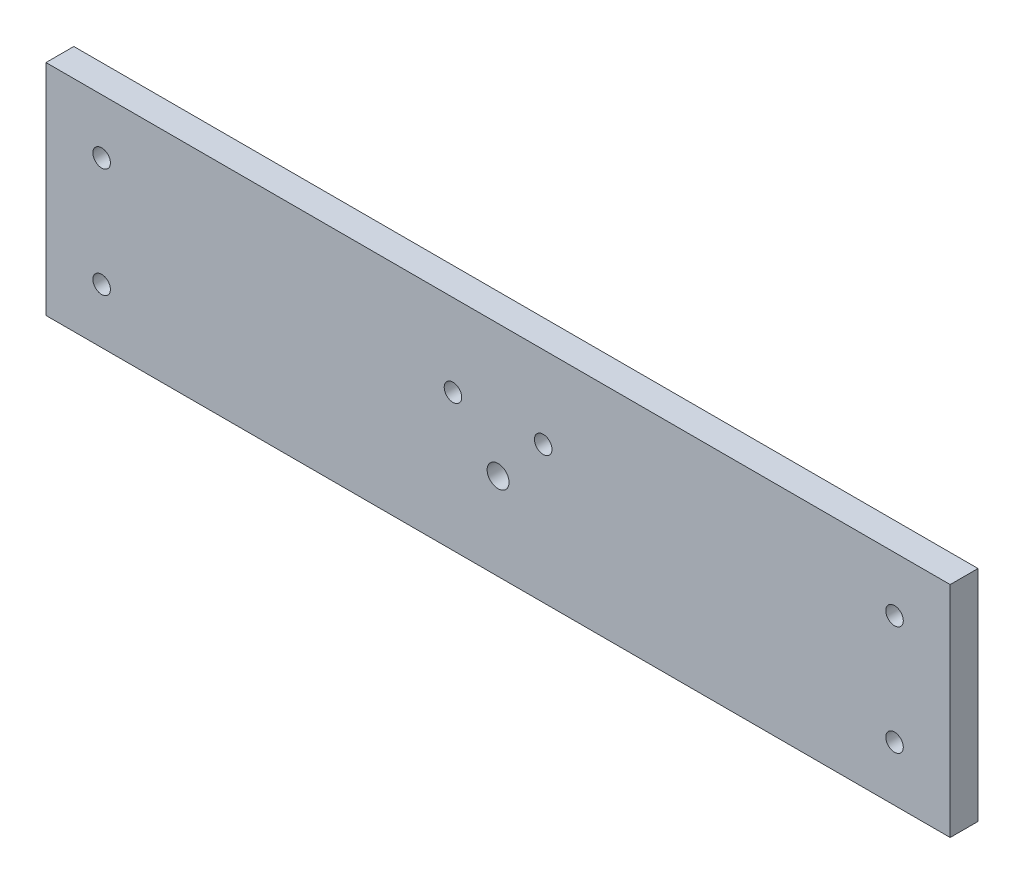
SolidWorks part; units mm, degrees
ref_plane "Front Plane" through (0, 0, 0) normal (0, 0, 1) x (1, 0, 0)
ref_plane "Top Plane" through (0, 0, 0) normal (0, 1, 0) x (1, 0, 0)
ref_plane "Right Plane" through (0, 0, 0) normal (1, 0, 0) x (0, 0, -1)
sketch "Sketch1" plane through (0, 0, 0) normal (0, 0, 1) x (1, 0, 0)
  line L0 (0, 50) -> (0, -50) construction
  line L1 (187.3, -50) -> (-187.3, -50)
  line L2 (187.3, -50) -> (187.3, 50) construction
  line L3 (187.3, 50) -> (-187.3, 50)
  line L4 (-187.3, -50) -> (-187.3, 50) construction
  line L5 (187.3, -50) -> (-187.3, 50) construction
  line L6 (187.3, 50) -> (-187.3, -50) construction
  line L7 (-206.35, -40) -> (206.35, -40) construction
  line L8 (206.35, -50) -> (-206.35, -50)
  line L9 (206.35, -50) -> (206.35, 50)
  line L10 (206.35, 50) -> (-206.35, 50)
  line L11 (-206.35, -50) -> (-206.35, 50)
  line L12 (206.35, -50) -> (-206.35, 50) construction
  line L13 (206.35, 50) -> (-206.35, -50) construction
  line L14 (-21.9118, -10.3015) -> (21.9118, -10.3015) construction
  line L15 (-15.026, 4.7245) -> (15.2028, -25.1508) construction
  line L16 (-30.052, -10.3015) -> (0, 19.7505) construction
  line L17 (-30.052, -10.3015) -> (-0.3536, -40) construction
  line L18 (0.3536, -40) -> (30.052, -10.3015) construction
  line L19 (0, 19.7505) -> (30.052, -10.3015) construction
  line L20 (-30.052, -10.3015) -> (30.052, -10.3015) construction
  line L21 (0, -40.3536) -> (0, 19.7505) construction
  line L22 (8.8388, -31.5147) -> (9.9707, -32.6466) construction
  line L23 (15.2028, -25.1508) -> (16.3347, -26.2826) construction
  line L24 (9.9707, -32.6466) -> (22.6986, -19.9187) construction
  line L25 (21.5668, -18.7868) -> (22.6986, -19.9187) construction
  line L26 (0.3536, -40) -> (8.8388, -31.5147) construction
  line L27 (30.052, -10.3015) -> (21.5668, -18.7868) construction
  line L28 (0.3536, -40) -> (-0.3536, -40)
  circle A0 centre (-20.5901, 12.5336) radius 4
  circle A1 centre (20.5901, 12.5336) radius 4
  circle A2 centre (0, -10.3015) radius 5
  point P0 (0, 0)
  point P8 (0, 0)
  point P21 (0, -10.3015)
  line B0 (-31.9435, -12.5466) -> (-27.4534, -8.0565) construction
  line B1 (-27.4534, -8.0565) -> (4.4901, -40) construction
  line B2 (-4.4901, -40) -> (-31.9435, -12.5466) construction
  line B3 (-4.4901, -40) -> (27.4534, -8.0565) construction
  line B4 (27.4534, -8.0565) -> (31.9435, -12.5466) construction
  line B5 (31.9435, -12.5466) -> (4.4901, -40) construction
  line B6 (-27.4534, -8.0565) -> (-27.4534, 19.397) construction
  line B7 (-27.4534, 19.397) -> (27.4534, 19.397) construction
  line B8 (27.4534, -8.0565) -> (27.4534, 19.397) construction
  circle B9 centre (20.5901, 12.5336) radius 4 construction
  circle B10 centre (-20.5901, 12.5336) radius 4 construction
  circle B11 centre (0, -10.3015) radius 13.462 construction
  circle B12 centre (-21.9118, -10.3015) radius 1.5541 construction
  circle B13 centre (0, -32.2133) radius 1.5541 construction
  circle B14 centre (21.9118, -10.3015) radius 1.5541 construction
  circle B15 centre (0, 11.6103) radius 1.5541 construction
  line B16 (-4.9282, 14.0459) -> (-24.3474, -5.3733) construction
  line B17 (-24.3474, -15.2297) -> (-4.9282, -34.649) construction
  line B18 (4.9282, -34.649) -> (24.3474, -15.2297) construction
  line B19 (24.3474, -5.3733) -> (4.9282, 14.0459) construction
  circle B20 centre (0, -32.2133) radius 1.5541 construction
  arc B21 (4.9282, 14.0459) -> (-4.9282, 14.0459) centre (0, -10.3015) ccw construction
  arc B22 (-24.3474, -5.3733) -> (-24.3474, -15.2297) centre (0, -10.3015) ccw construction
  arc B23 (-4.9282, -34.649) -> (4.9282, -34.649) centre (0, -10.3015) ccw construction
  arc B24 (24.3474, -15.2297) -> (24.3474, -5.3733) centre (0, -10.3015) ccw construction
  circle B25 centre (0, -10.3015) radius 13.462 construction
  circle B26 centre (21.9118, -10.3015) radius 1.5541 construction
  circle B27 centre (0, 11.6103) radius 1.5541 construction
  circle B28 centre (-21.9118, -10.3015) radius 1.5541 construction
  dimension "D6" = 10
  dimension "D1" = 374.6
  dimension "D2" = 19.05
  dimension "D3" = 10
  dimension "D4" = 100
  dimension "D5" = 42.5
  dimension "D7" = 9
sketch_block_instance "Fold pattern - Angle Mount v3-1"
sketch_block "Fold pattern - Angle Mount v3"
sketch_block_instance "nema 17 mount dxf-1"
sketch_block "nema 17 mount dxf"
extrude "Boss-Extrude1" add sketch "Sketch1" along normal blind 12.7 contours L11 L8 L1 L9 L10 L3 A1 A0 L26 L28 L17 L16 L19 L27 L25 L24 L22
sketch "Sketch2" plane through (0, 0, 12.7) normal (0, 0, 1) x (1, 0, 0)
  line L0 (-206.35, 50) -> (-206.35, -50) construction
  line L1 (206.35, 50) -> (-206.35, 50) construction
  line L2 (206.35, -50) -> (-206.35, -50) construction
  line L4 (-180.95, 50) -> (-180.95, -50) construction
  line L5 (-206.35, -50) -> (-155.55, -50) construction
  line L6 (-206.35, -50) -> (-206.35, 50) construction
  line L7 (-206.35, 50) -> (-155.55, 50) construction
  line L8 (-155.55, -50) -> (-155.55, 50) construction
  line L9 (-206.35, 0) -> (-155.55, 0) construction
  line L10 (0, 50) -> (0, -50) construction
  line L11 (206.35, 0) -> (155.55, 0) construction
  line L12 (155.55, -50) -> (155.55, 50) construction
  line L13 (206.35, 50) -> (155.55, 50) construction
  line L14 (206.35, -50) -> (206.35, 50) construction
  line L15 (206.35, -50) -> (155.55, -50) construction
  line L16 (180.95, 50) -> (180.95, -50) construction
  line L17 (206.35, 50) -> (206.35, -50) construction
  line L18 (-206.35, -50) -> (-206.35, 50) construction
  circle A0 centre (-180.95, 25) radius 4
  circle A1 centre (-180.95, -25) radius 4
  circle A2 centre (180.95, -25) radius 4
  circle A3 centre (180.95, 25) radius 4
  dimension "D4" = 8
  dimension "D2" = 50.8
  dimension "D3" = 25
extrude "Cut-Extrude1" cut sketch "Sketch2" against normal up to next
sketch "Sketch3" plane through (0, 0, 12.7) normal (0, 0, 1) x (1, 0, 0)
  point P20 (0, -10.3015)
  line B0 (-21.9118, -10.3015) -> (21.9118, -10.3015) construction
  line B1 (-15.026, 4.7245) -> (15.026, -25.3275) construction
  line B2 (-30.052, -10.3015) -> (0, 19.7505)
  line B3 (-30.052, -10.3015) -> (0, -40.3536)
  line B4 (0, -40.3536) -> (30.052, -10.3015) construction
  line B5 (0, 19.7505) -> (30.052, -10.3015)
  line B6 (-30.052, -10.3015) -> (30.052, -10.3015) construction
  line B7 (0, -40.3536) -> (0, 19.7505) construction
  line B8 (8.6621, -31.6915) -> (14.3189, -37.3483)
  line B9 (15.026, -25.3275) -> (20.6829, -30.9844) construction
  line B10 (14.3189, -37.3483) -> (27.0468, -24.6204)
  line B11 (21.39, -18.9636) -> (27.0468, -24.6204)
  line B12 (0, -40.3536) -> (8.6621, -31.6915)
  line B13 (30.052, -10.3015) -> (21.39, -18.9636)
  circle B14 centre (-20.5901, 12.5336) radius 4
  circle B15 centre (20.5901, 12.5336) radius 4
  line B16 (-4.9282, 14.0459) -> (-24.3474, -5.3733) construction
  line B17 (-24.3474, -15.2297) -> (-4.9282, -34.649) construction
  line B18 (4.9282, -34.649) -> (24.3474, -15.2297) construction
  line B19 (24.3474, -5.3733) -> (4.9282, 14.0459) construction
  circle B20 centre (0, -32.2133) radius 1.5541 construction
  arc B21 (4.9282, 14.0459) -> (-4.9282, 14.0459) centre (0, -10.3015) ccw construction
  arc B22 (-24.3474, -5.3733) -> (-24.3474, -15.2297) centre (0, -10.3015) ccw construction
  arc B23 (-4.9282, -34.649) -> (4.9282, -34.649) centre (0, -10.3015) ccw construction
  arc B24 (24.3474, -15.2297) -> (24.3474, -5.3733) centre (0, -10.3015) ccw construction
  circle B25 centre (0, -10.3015) radius 13.462 construction
  circle B26 centre (21.9118, -10.3015) radius 1.5541 construction
  circle B27 centre (0, 11.6103) radius 1.5541 construction
  circle B28 centre (-21.9118, -10.3015) radius 1.5541 construction
  line B29 (-31.9435, -12.5466) -> (-27.4534, -8.0565) construction
  line B30 (-27.4534, -8.0565) -> (4.4901, -40) construction
  line B31 (-4.4901, -40) -> (-31.9435, -12.5466) construction
  line B32 (-4.4901, -40) -> (27.4534, -8.0565) construction
  line B33 (27.4534, -8.0565) -> (31.9435, -12.5466) construction
  line B34 (31.9435, -12.5466) -> (4.4901, -40) construction
  line B35 (-27.4534, -8.0565) -> (-27.4534, 19.397) construction
  line B36 (-27.4534, 19.397) -> (27.4534, 19.397) construction
  line B37 (27.4534, -8.0565) -> (27.4534, 19.397) construction
  circle B38 centre (20.5901, 12.5336) radius 4 construction
  circle B39 centre (-20.5901, 12.5336) radius 4 construction
  circle B40 centre (0, -10.3015) radius 13.462 construction
  circle B41 centre (-21.9118, -10.3015) radius 1.5541 construction
  circle B42 centre (0, -32.2133) radius 1.5541 construction
  circle B43 centre (21.9118, -10.3015) radius 1.5541 construction
  circle B44 centre (0, 11.6103) radius 1.5541 construction
sketch_block_instance "Block1-1"
sketch_block "Block1"
sketch_block_instance "nema 17 mount dxf-2"
sketch_block_instance "Fold pattern - Angle Mount v3-2"
extrude "Cut-Extrude2" [suppressed] cut sketch "Sketch3" against normal up to next
fillet "Fillet1" [suppressed] radius 4
